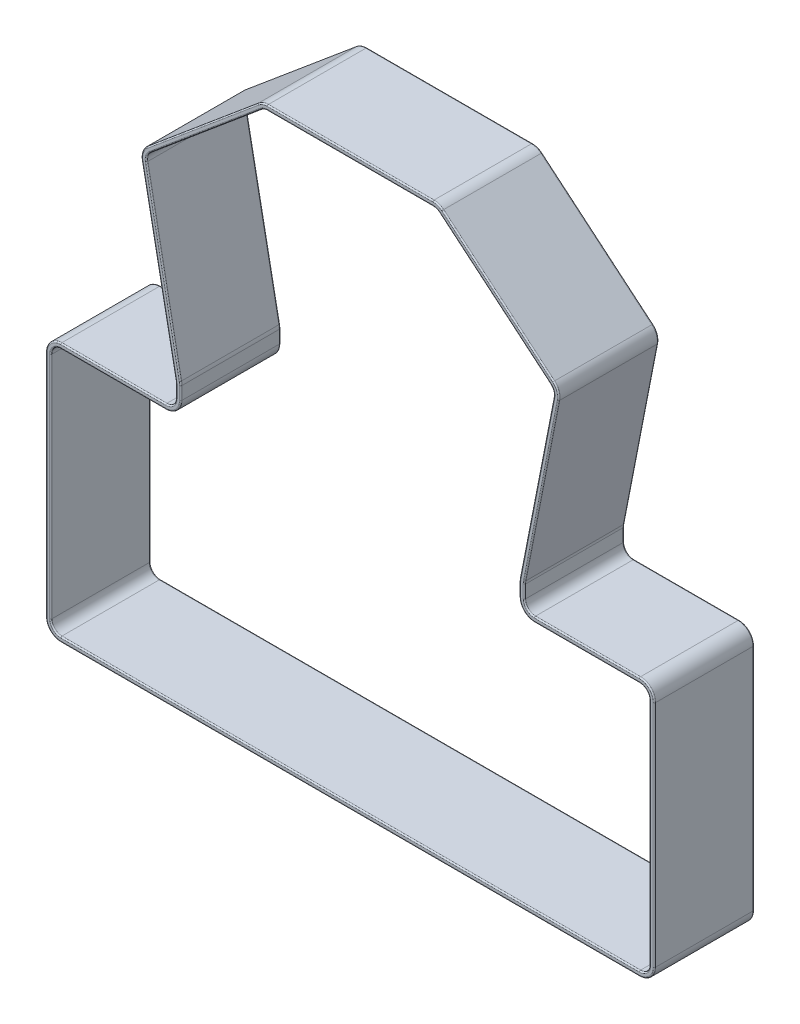
SolidWorks part; units mm, degrees
ref_plane "Front Plane" through (0, 0, 0) normal (0, 0, 1) x (1, 0, 0)
ref_plane "Top Plane" through (0, 0, 0) normal (0, 1, 0) x (1, 0, 0)
ref_plane "Right Plane" through (0, 0, 0) normal (1, 0, 0) x (0, 0, -1)
sketch "Sketch1" plane through (0, 0, 0) normal (0, 0, 1) x (1, 0, 0)
  line L0 (8.3, 10) -> (-8.3, 10)
  line L1 (8.3, 10) -> (-8.3, 10) construction
  line L2 (-8.942, 9.7667) -> (-20.0597, 0.4582)
  line L3 (-20.3993, -0.5) -> (-17.0127, -17.8601)
  line L4 (-16.9757, -18.2431) -> (-16.9757, -19.5299)
  line L5 (-18.4757, -21.0299) -> (-29, -21.0299)
  line L6 (-30, -22.0299) -> (-30, -44.9985)
  line L7 (-29, -45.9985) -> (29, -45.9985)
  line L8 (30, -22.0299) -> (30, -44.9985)
  line L9 (-29, -46) -> (-29, -45) construction
  line L10 (-36.7619, -0.5) -> (-16.9095, -0.5) construction
  line L11 (0, 10) -> (0, -45.9985) construction
  line L12 (18.4757, -21.0299) -> (29, -21.0299)
  line L13 (16.9757, -18.2431) -> (16.9757, -19.5299)
  line L14 (20.3993, -0.5) -> (17.0127, -17.8601)
  line L15 (8.942, 9.7667) -> (20.0597, 0.4582)
  line L16 (-16.9757, -19) -> (-16.9757, -21) construction
  arc A0 (-30, -44.9985) -> (-29, -45.9985) centre (-29, -44.9985) ccw
  arc A1 (-29, -21.0299) -> (-30, -22.0299) centre (-29, -22.0299) ccw
  arc A2 (-8.3, 10) -> (-8.942, 9.7667) centre (-8.3, 9) ccw
  arc A3 (-20.0597, 0.4582) -> (-20.3993, -0.5) centre (-19.4178, -0.3085) ccw
  arc A4 (-17.0127, -17.8601) -> (-16.9757, -18.2431) centre (-18.9757, -18.2431) cw
  arc A5 (-16.9757, -19.5299) -> (-18.4757, -21.0299) centre (-18.4757, -19.5299) cw
  arc A6 (16.9757, -19.5299) -> (18.4757, -21.0299) centre (18.4757, -19.5299) ccw
  arc A7 (17.0127, -17.8601) -> (16.9757, -18.2431) centre (18.9757, -18.2431) ccw
  arc A8 (20.0597, 0.4582) -> (20.3993, -0.5) centre (19.4178, -0.3085) cw
  arc A9 (8.3, 10) -> (8.942, 9.7667) centre (8.3, 9) cw
  arc A10 (29, -21.0299) -> (30, -22.0299) centre (29, -22.0299) cw
  arc A11 (30, -44.9985) -> (29, -45.9985) centre (29, -44.9985) cw
  dimension "D1" = 1
  dimension "D2" = 1
  dimension "D3" = 1
  dimension "D4" = 1
  dimension "D5" = 2
  dimension "D6" = 1.5
sketch "Sketch2" plane through (0, 0, 0) normal (1, 0, 0) x (0, 0, -1)
  line L0 (-26.75, 10) -> (26.75, 10) construction
  line L1 (-4.875, 10.5) -> (4.875, 10.5)
  line L2 (-5, 10.375) -> (-5, 10.125)
  line L3 (-4.875, 10) -> (4.875, 10)
  line L4 (5, 10.375) -> (5, 10.125)
  line L5 (-5, 10.5) -> (5, 10) construction
  line L6 (-5, 10) -> (5, 10.5) construction
  line L7 (0, 10) -> (0, 9.7667) construction
  arc A0 (4.875, 10.5) -> (5, 10.375) centre (4.875, 10.375) cw
  arc A1 (4.875, 10) -> (5, 10.125) centre (4.875, 10.125) ccw
  arc A2 (-5, 10.125) -> (-4.875, 10) centre (-4.875, 10.125) ccw
  arc A3 (-4.875, 10.5) -> (-5, 10.375) centre (-4.875, 10.375) ccw
  point P0 (0, 10.25)
  point P9 (0, 10)
  dimension "D3" = 0.125
  dimension "D1" = 0.5
  dimension "D2" = 10
sweep "Sweep2" add profiles "Sketch2" path "Sketch1"
